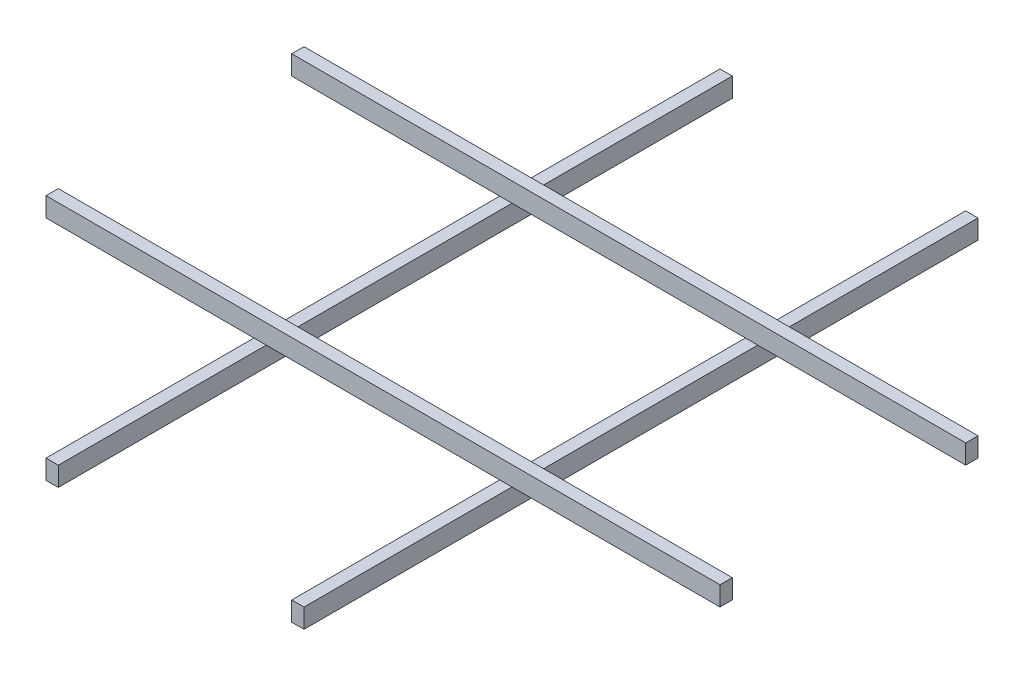
SolidWorks part; units mm, degrees
material "Doug Fir"
ref_plane "Front Plane" through (0, 0, 0) normal (0, 0, 1) x (1, 0, 0)
ref_plane "Top Plane" through (0, 0, 0) normal (0, 1, 0) x (1, 0, 0)
ref_plane "Right Plane" through (0, 0, 0) normal (1, 0, 0) x (0, 0, -1)
sketch "Lower Level" plane through (0, 0, 0) normal (0, 1, 0) x (1, 0, 0)
  line L0 (1244.6, 0) -> (1244.6, 4876.8)
  line L1 (3022.6, 0) -> (3022.6, 4876.8)
  line L2 (1244.6, 2438.4) -> (3022.6, 2438.4) construction
  point P7 (2133.6, 2438.4)
  dimension "D1" = 4876.8
  dimension "D2" = 889
ref_plane "Plane2" through (0, 139.7, 0) normal (0, 1, 0) x (1, 0, 0)
sketch "Sketch12" plane through (0, 139.7, 0) normal (0, 1, 0) x (1, 0, 0)
  line L0 (-304.8, 3327.4) -> (4572, 3327.4)
  line L1 (4572, 1549.4) -> (-304.8, 1549.4)
  line L2 (2133.6, 3327.4) -> (2133.6, 1549.4) construction
  point P0 (2133.6, 2438.4)
  point P6 (2133.6, 1549.4)
  point P7 (2133.6, 3327.4)
  point P10 (2133.6, 2438.4)
  dimension "D1" = 4876.8
  dimension "D2" = 889
other "Profiles 4X6(1)"
ref_plane "Plane1" through (1244.6, 0, 0) normal (0, 0, -1) x (-1, 0, 0)
sketch "Sketch1" plane through (1244.6, 0, 0) normal (0, 0, -1) x (-1, 0, 0)
  line L1 (-44.45, 69.85) -> (44.45, 69.85)
  line L2 (-44.45, 69.85) -> (-44.45, -69.85)
  line L3 (-44.45, -69.85) -> (44.45, -69.85)
  line L4 (44.45, 69.85) -> (44.45, -69.85)
  line L5 (-44.45, 69.85) -> (44.45, -69.85) construction
  line L6 (-44.45, -69.85) -> (44.45, 69.85) construction
  point P0 (0, 0)
  point P6 (0, 69.85)
  point P7 (0, -69.85)
  point P8 (44.45, 0)
  point P9 (-44.45, 0)
  point P10 (0, 0)
  dimension "D1" = 88.9
  dimension "D2" = 139.7
sketch3d "3DSketch2"
  line L0 (2133.6, 139.7, -2438.4) -> (2133.6, 0, -2438.4)
  line L1 (1244.6, 0, -2438.4) -> (3022.6, 0, -2438.4) construction
equation "\"Width\" = 35"
equation "\"Length\"=192"
equation "\"D1@Lower Level\"=\"Length\""
equation "\"D2@Lower Level\"=\"Width\""
equation "\"D1@Sketch12\"=\"Length\""
equation "\"D2@Sketch12\"=\"Width\""
